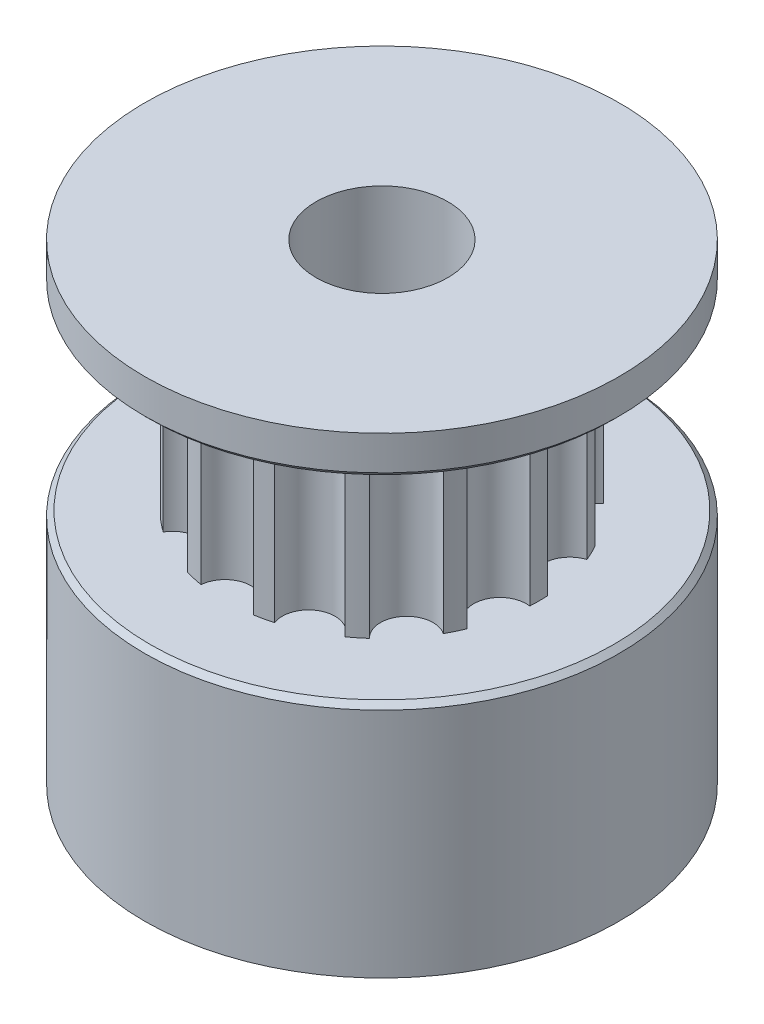
SolidWorks part; units mm, degrees
ref_plane "前视基准面" through (0, 0, 0) normal (0, 0, 1) x (1, 0, 0)
ref_plane "上视基准面" through (0, 0, 0) normal (0, 1, 0) x (1, 0, 0)
ref_plane "右视基准面" through (0, 0, 0) normal (1, 0, 0) x (0, 0, -1)
sketch "草图2" plane through (0, 0, 0) normal (0, 1, 0) x (1, 0, 0)
  circle A0 centre (0, 0) radius 9
  dimension "D1" = 18
extrude "凸台-拉伸1" add sketch "草图2" along normal blind 9
sketch "草图3" plane through (0, 9, 0) normal (0, 1, 0) x (1, 0, 0)
  arc A0 (-3.4442, 4.8553) -> (-3.9672, 4.4382) centre (0, 0) ccw
  arc A1 (-0.9965, 5.8689) -> (0.9965, 5.8689) centre (0, 5.9528) ccw
  arc A2 (1.6486, 5.72) -> (3.4442, 4.8553) centre (2.5828, 5.3633) ccw
  arc A3 (3.9672, 4.4382) -> (5.2097, 2.8801) centre (4.6541, 3.7115) ccw
  arc A4 (5.5, 2.2774) -> (5.9434, 0.3345) centre (5.8036, 1.3246) ccw
  arc A5 (5.9434, -0.3345) -> (5.5, -2.2774) centre (5.8036, -1.3246) ccw
  arc A6 (5.2097, -2.8801) -> (3.9672, -4.4382) centre (4.6541, -3.7115) ccw
  arc A7 (3.4442, -4.8553) -> (1.6486, -5.72) centre (2.5828, -5.3633) ccw
  arc A8 (0.9965, -5.8689) -> (-0.9965, -5.8689) centre (0, -5.9528) ccw
  arc A9 (-1.6486, -5.72) -> (-3.4442, -4.8553) centre (-2.5828, -5.3633) ccw
  arc A10 (-3.9672, -4.4382) -> (-5.2097, -2.8801) centre (-4.6541, -3.7115) ccw
  arc A11 (-5.5, -2.2774) -> (-5.9434, -0.3345) centre (-5.8036, -1.3246) ccw
  arc A12 (-5.9434, 0.3345) -> (-5.5, 2.2774) centre (-5.8036, 1.3246) ccw
  arc A13 (-5.2097, 2.8801) -> (-3.9672, 4.4382) centre (-4.6541, 3.7115) ccw
  arc A14 (-3.4442, 4.8553) -> (-1.6486, 5.72) centre (-2.5828, 5.3633) ccw
  arc A15 (-0.9965, 5.8689) -> (-1.6486, 5.72) centre (0, 0) ccw
  arc A16 (1.6486, 5.72) -> (0.9965, 5.8689) centre (0, 0) ccw
  arc A17 (3.9672, 4.4382) -> (3.4442, 4.8553) centre (0, 0) ccw
  arc A18 (5.5, 2.2774) -> (5.2097, 2.8801) centre (0, 0) ccw
  arc A19 (5.9434, -0.3345) -> (5.9434, 0.3345) centre (0, 0) ccw
  arc A20 (5.2097, -2.8801) -> (5.5, -2.2774) centre (0, 0) ccw
  arc A21 (3.4442, -4.8553) -> (3.9672, -4.4382) centre (0, 0) ccw
  arc A22 (0.9965, -5.8689) -> (1.6486, -5.72) centre (0, 0) ccw
  arc A23 (-1.6486, -5.72) -> (-0.9965, -5.8689) centre (0, 0) ccw
  arc A24 (-3.9672, -4.4382) -> (-3.4442, -4.8553) centre (0, 0) ccw
  arc A25 (-5.5, -2.2774) -> (-5.2097, -2.8801) centre (0, 0) ccw
  arc A26 (-5.9434, 0.3345) -> (-5.9434, -0.3345) centre (0, 0) ccw
  arc A27 (-5.2097, 2.8801) -> (-5.5, 2.2774) centre (0, 0) ccw
  point P34 (0, 0)
  dimension "D1" = 2
  dimension "D2" = 14
extrude "凸台-拉伸2" add sketch "草图3" along normal blind 7.4
sketch "草图4" plane through (0, 16.4, 0) normal (0, 1, 0) x (1, 0, 0)
  circle A0 centre (0, 0) radius 9
extrude "凸台-拉伸3" add sketch "草图4" along normal blind 1.5
sketch "草图5" plane through (0, 17.9, 0) normal (0, 1, 0) x (1, 0, 0)
  circle A0 centre (0, 0) radius 2.5
  dimension "D1" = 5
extrude "切除-拉伸1" cut sketch "草图5" against normal through all
chamfer "倒角1" distance 0.2 angle 45 2 edges at (0, 16.4, 9) (0, 9, 9)
